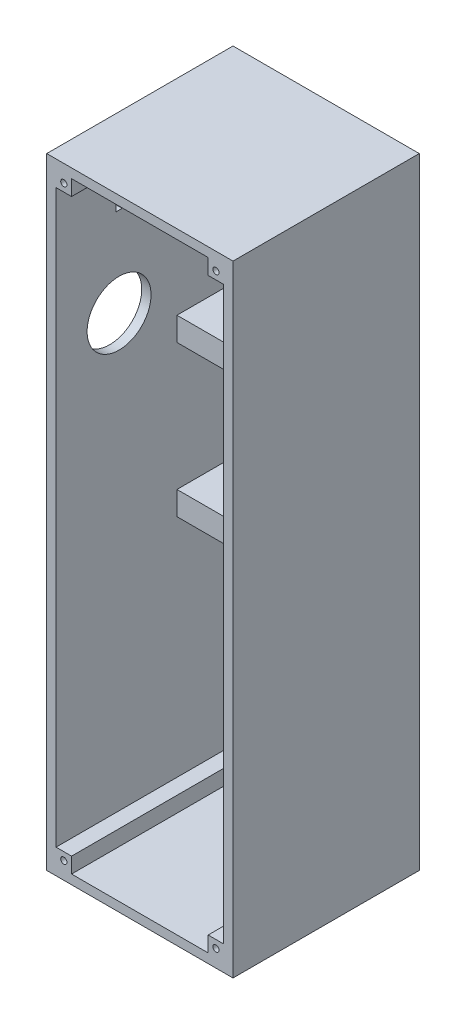
SolidWorks part; units mm, degrees
ref_plane "Płaszczyzna przednia" through (0, 0, 0) normal (0, 0, 1) x (1, 0, 0)
ref_plane "Płaszczyzna górna" through (0, 0, 0) normal (0, 1, 0) x (1, 0, 0)
ref_plane "Płaszczyzna prawa" through (0, 0, 0) normal (1, 0, 0) x (0, 0, -1)
sketch "Szkic1" plane through (0, 0, 0) normal (0, 1, 0) x (1, 0, 0)
  line L1 (0, 0) -> (60, 0)
  line L2 (0, 0) -> (0, 60)
  line L3 (0, 60) -> (60, 60)
  line L4 (60, 0) -> (60, 60)
  dimension "D1" = 60
  dimension "D2" = 60
extrude "Dodanie-wyciągnięcie1" add sketch "Szkic1" along normal blind 200
shell "Skorupa1" thickness 3
sketch "Szkic2" plane through (0, 0, -57) normal (0, 0, 1) x (1, 0, 0)
  line L0 (3, 197) -> (3, 192) construction
  line L1 (3, 197) -> (3, 3) construction
  line L2 (5.5, 194.5) -> (5.5, 197) construction
  line L3 (3, 197) -> (8, 197)
  line L4 (3, 197) -> (3, 192)
  line L5 (3, 192) -> (8, 192)
  line L6 (8, 197) -> (8, 192)
  circle A0 centre (5.5, 194.5) radius 1
  dimension "D3" = 2
  dimension "D1" = 5
  dimension "D2" = 5
extrude "Dodanie-wyciągnięcie5" add sketch "Szkic2" along normal blind 57
sketch "Szkic3" plane through (0, 0, -57) normal (0, 0, 1) x (1, 0, 0)
  line L1 (57, 197) -> (52, 197)
  line L2 (57, 197) -> (57, 192)
  line L3 (57, 192) -> (52, 192)
  line L4 (52, 197) -> (52, 192)
  circle A0 centre (54.5, 194.5) radius 1
  dimension "D2" = 2
  dimension "D1" = 5
extrude "Dodanie-wyciągnięcie6" add sketch "Szkic3" along normal blind 57
sketch "Szkic4" plane through (0, 0, 0) normal (0, 0, 1) x (1, 0, 0)
  line L1 (3, 3) -> (8, 3)
  line L2 (3, 3) -> (3, 8)
  line L3 (3, 8) -> (8, 8)
  line L4 (8, 3) -> (8, 8)
  circle A0 centre (5.5, 5.5) radius 1
  dimension "D2" = 2
  dimension "D1" = 5
extrude "Dodanie-wyciągnięcie7" add sketch "Szkic4" against normal blind 57
sketch "Szkic5" plane through (0, 0, -57) normal (0, 0, 1) x (1, 0, 0)
  line L0 (54.5, 8) -> (54.5, 3) construction
  line L1 (57, 3) -> (52, 3)
  line L2 (57, 3) -> (57, 8)
  line L3 (57, 8) -> (52, 8)
  line L4 (52, 3) -> (52, 8)
  circle A0 centre (54.5, 5.5) radius 1
  dimension "D2" = 2
  dimension "D1" = 5
extrude "Dodanie-wyciągnięcie8" add sketch "Szkic5" along normal blind 57
sketch "Szkic10" plane through (0, 0, 0) normal (-1, 0, 0) x (0, 0, 1)
  line L0 (0, 200) -> (0, 146.82) construction
  line L1 (0, 200) -> (0, 0) construction
  line L2 (0, 146.82) -> (-20.3, 146.82) construction
  circle A0 centre (-20.3, 146.82) radius 10.3
  dimension "D3" = 20.6
  dimension "D1" = 53.18
  dimension "D2" = 20.3
extrude "Wytnij-wyciągnięcie3" cut sketch "Szkic10" against normal blind 3
sketch "Szkic12" plane through (57, 0, 0) normal (-1, 0, 0) x (0, 0, 1)
  line L0 (0, 192) -> (-57, 192) construction
  line L1 (-57, 156.82) -> (-11.45, 156.82)
  line L2 (-57, 156.82) -> (-57, 164.42)
  line L3 (-57, 164.42) -> (-11.45, 164.42)
  line L4 (-11.45, 156.82) -> (-11.45, 164.42)
  line L5 (0, 192) -> (0, 8) construction
  line L7 (-57, 115.82) -> (-11.45, 115.82)
  line L8 (-57, 115.82) -> (-57, 108.22)
  line L9 (-57, 108.22) -> (-11.45, 108.22)
  line L10 (-11.45, 115.82) -> (-11.45, 108.22)
  line L11 (0, 197) -> (-57, 197) construction
  dimension "D1" = 45.55
  dimension "D2" = 7.6
  dimension "D3" = 40.18
  dimension "D4" = 11.45
  dimension "D5" = 45.55
  dimension "D6" = 7.6
  dimension "D7" = 76.18
  dimension "D8" = 11.45
extrude "Dodanie-wyciągnięcie9" add sketch "Szkic12" along normal blind 26.5
sketch "Szkic13" plane through (30.5, 0, 0) normal (-1, 0, 0) x (0, 0, 1)
  line L0 (-11.45, 164.42) -> (-57, 164.42) construction
  line L1 (-11.45, 156.82) -> (-11.45, 164.42) construction
  circle A2 centre (-15.45, 162.42) radius 1.5
  circle A3 centre (-25.1, 162.42) radius 1.5
  dimension "D1" = 3
  dimension "D2" = 4
  dimension "D3" = 3
  dimension "D4" = 13.65
  dimension "D5" = 2
  dimension "D6" = 2
extrude "Wytnij-wyciągnięcie4" cut sketch "Szkic13" against normal blind 5
sketch "Szkic15" plane through (30.5, 0, 0) normal (-1, 0, 0) x (0, 0, 1)
  line L1 (-11.45, 108.22) -> (-11.45, 115.82) construction
  line L3 (-57, 108.22) -> (-11.45, 108.22) construction
  circle A0 centre (-15.45, 111.22) radius 1.5
  circle A1 centre (-25.1, 111.22) radius 1.5
  dimension "D1" = 3
  dimension "D2" = 4
  dimension "D3" = 3
  dimension "D5" = 3
  dimension "D6" = 3
  dimension "D4" = 13.65
extrude "Wytnij-wyciągnięcie5" cut sketch "Szkic15" against normal blind 5
sketch "Szkic16" plane through (0, 164.42, 0) normal (0, 1, 0) x (1, 0, 0)
  line L0 (30.5, 11.45) -> (48, 11.45) construction
  line L1 (30.5, 11.45) -> (57, 11.45) construction
  line L2 (57, 11.45) -> (57, 26.45)
  line L3 (48, 11.45) -> (57, 26.45)
  line L4 (48, 11.45) -> (57, 11.45)
  dimension "D1" = 17.5
  dimension "D2" = 15
extrude "Wytnij-wyciągnięcie6" cut sketch "Szkic16" against normal blind 10
sketch "Szkic17" plane through (0, 0, 0) normal (-1, 0, 0) x (0, 0, 1)
  line L0 (-20.3, 157.12) -> (-20.3, 200) construction
  line L1 (-60, 200) -> (0, 200) construction
  line L3 (-21.3, 181.56) -> (-19.3, 181.56)
  line L4 (-21.3, 181.56) -> (-21.3, 175.56)
  line L5 (-21.3, 175.56) -> (-19.3, 175.56)
  line L6 (-19.3, 181.56) -> (-19.3, 175.56)
  line L7 (-21.3, 181.56) -> (-19.3, 175.56) construction
  line L8 (-21.3, 175.56) -> (-19.3, 181.56) construction
  circle A0 centre (-20.3, 146.82) radius 10.3 construction
  point P7 (-20.3, 178.56)
  dimension "D1" = 6
  dimension "D2" = 2
extrude "Wytnij-wyciągnięcie7" cut sketch "Szkic17" against normal blind 10
